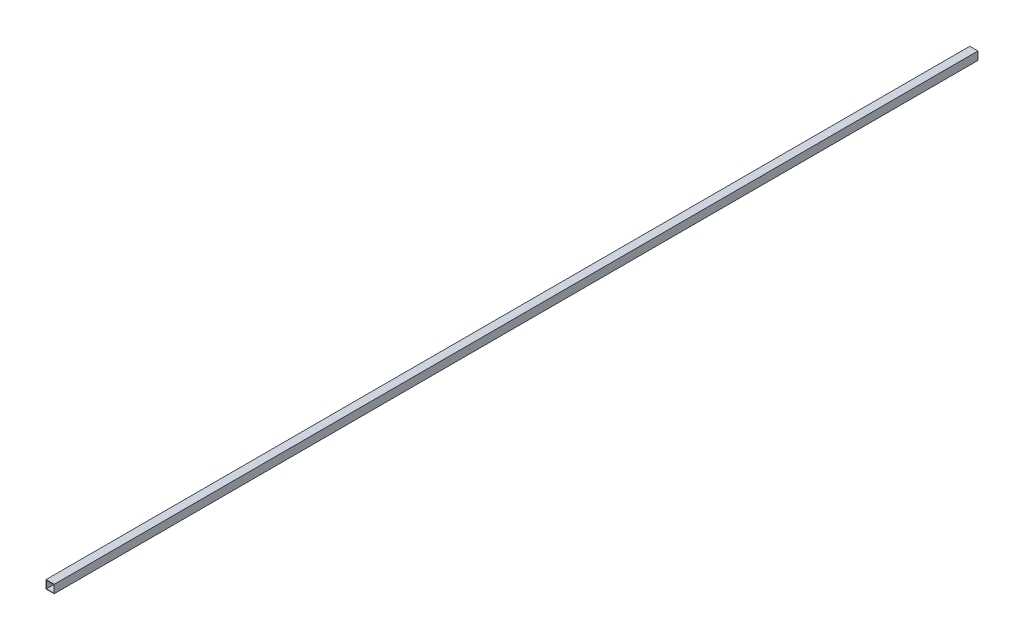
SolidWorks part; units mm, degrees
material "1100-H18 棒材(SS)"
ref_plane "前视基准面" through (0, 0, 0) normal (0, 0, 1) x (1, 0, 0)
ref_plane "上视基准面" through (0, 0, 0) normal (0, 1, 0) x (1, 0, 0)
ref_plane "右视基准面" through (0, 0, 0) normal (1, 0, 0) x (0, 0, -1)
other "Configuration Table"
sketch "草图1" plane through (0, 0, 0) normal (0, 0, 1) x (1, 0, 0)
  line L1 (0, 0) -> (20, 0)
  line L2 (0, 0) -> (0, 20)
  line L3 (0, 20) -> (20, 20)
  line L4 (20, 0) -> (20, 20)
  line L5 (1, 1) -> (19, 1)
  line L6 (1, 1) -> (1, 19)
  line L7 (1, 19) -> (19, 19)
  line L8 (19, 1) -> (19, 19)
  dimension "D1" = 20
  dimension "D2" = 20
  dimension "D3" = 1
  dimension "D4" = 1
  dimension "D5" = 1
  dimension "D6" = 1
extrude "凸台-拉伸1" add sketch "草图1" along normal blind 2250
